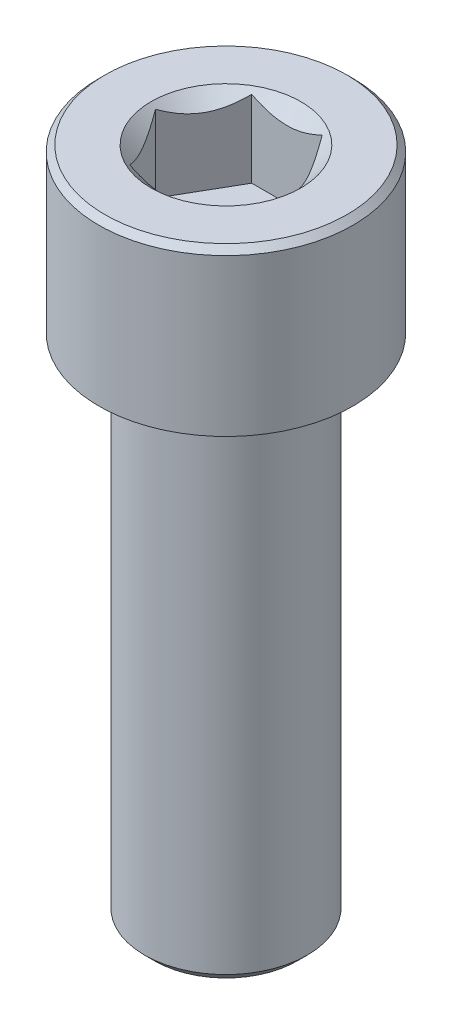
SolidWorks part; units mm, degrees
ref_plane "Płaszczyzna przednia" through (0, 0, 0) normal (0, 0, 1) x (1, 0, 0)
ref_plane "Płaszczyzna górna" through (0, 0, 0) normal (0, 1, 0) x (1, 0, 0)
ref_plane "Płaszczyzna prawa" through (0, 0, 0) normal (1, 0, 0) x (0, 0, -1)
sketch "Szkic1" plane through (0, 0, 0) normal (0, 0, 1) x (1, 0, 0)
  line L0 (0, 0) -> (0, 67.7826) construction
  line L1 (0, 0) -> (-4, 0)
  line L2 (-4, 0) -> (-4, 25)
  line L3 (-4, 25) -> (-6.25, 25)
  line L4 (-6.25, 25) -> (-6.25, 33)
  line L5 (-6.25, 33) -> (0, 33)
  line L6 (0, 33) -> (0, 0)
  dimension "D1" = 12.5
  dimension "D2" = 8
  dimension "D3" = 8
  dimension "D4" = 25
revolve "Obrót1" add sketch "Szkic1" angle 360 about L0
cosmetic thread "Oznaczenie gwintu1" parameters "D2"=6.619
sketch "Szkic2" plane through (0, 33, 0) normal (0, 1, 0) x (1, 0, 0)
  line L0 (0, 0) -> (5.3969, 0) construction
  line L1 (3.4641, 0) -> (1.7321, 3)
  line L2 (1.7321, 3) -> (-1.7321, 3)
  line L3 (-1.7321, 3) -> (-3.4641, 0)
  line L4 (-3.4641, 0) -> (-1.7321, -3)
  line L5 (-1.7321, -3) -> (1.7321, -3)
  line L6 (1.7321, -3) -> (3.4641, 0)
  circle A0 centre (0, 0) radius 3 construction
  dimension "D1" = 6
extrude "Wyciągnięcie1" cut sketch "Szkic2" against normal blind 4
chamfer "Sfazowanie1" distance 0.3 angle 45 1 edges at (0, 33, -6.25)
sketch "Szkic3" plane through (0, 33, 0) normal (0, 1, 0) x (1, 0, 0)
  circle A0 centre (0, 0) radius 3.6817
extrude "Wytnij-wyciągnięcie1" cut sketch "Szkic3" against normal blind 2 draft 45
chamfer "Sfazowanie2" distance 0.5 angle 45 1 edges at (0, 0, -4)
